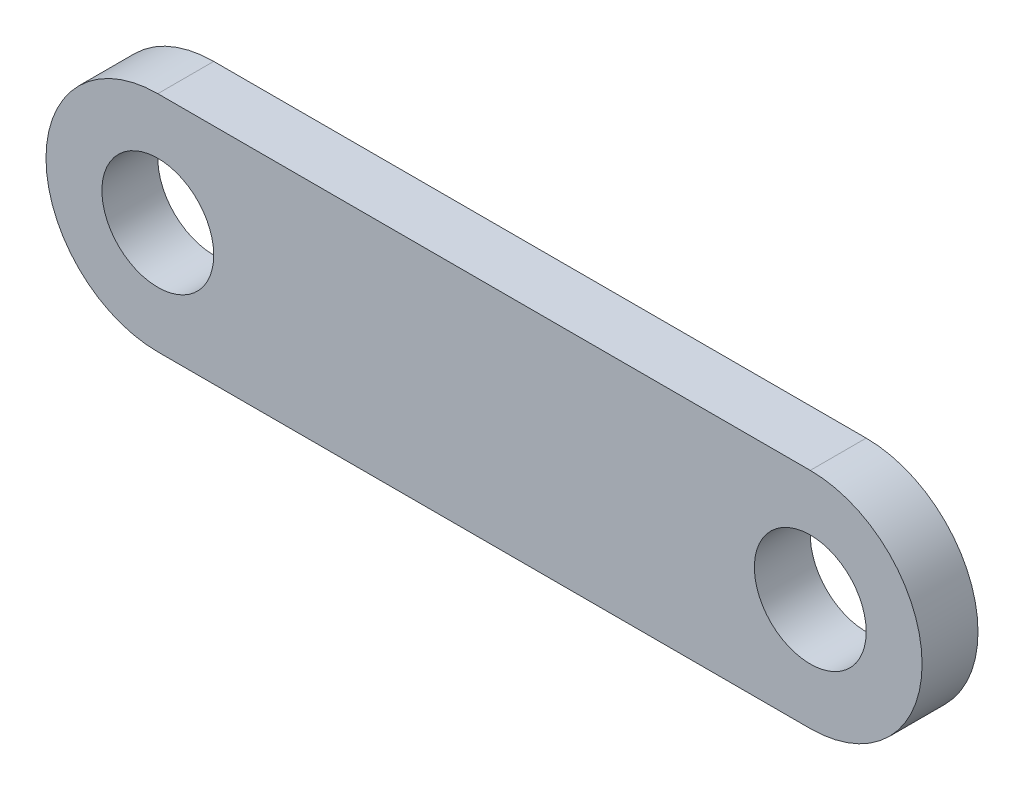
SolidWorks part; units mm, degrees
ref_plane "Plano frontal" through (0, 0, 0) normal (0, 0, 1) x (1, 0, 0)
ref_plane "Plano superior" through (0, 0, 0) normal (0, 1, 0) x (1, 0, 0)
ref_plane "Plano direito" through (0, 0, 0) normal (1, 0, 0) x (0, 0, -1)
sketch "Esboço1" plane through (0, 0, 0) normal (0, 0, 1) x (1, 0, 0)
  line L0 (-5.835, 2) -> (5.835, 2)
  line L1 (-5.835, 0) -> (5.835, 0) construction
  line L2 (-5.835, -2) -> (5.835, -2)
  arc A0 (-5.835, 2) -> (-5.835, -2) centre (-5.835, 0) ccw
  arc A1 (5.835, 2) -> (5.835, -2) centre (5.835, 0) cw
  circle A2 centre (-5.835, 0) radius 1
  circle A3 centre (5.835, 0) radius 1
  point P3 (0, 2)
  dimension "D2" = 2
  dimension "D1" = 11.67
extrude "Ressalto-extrusão1" add sketch "Esboço1" along normal blind 1
